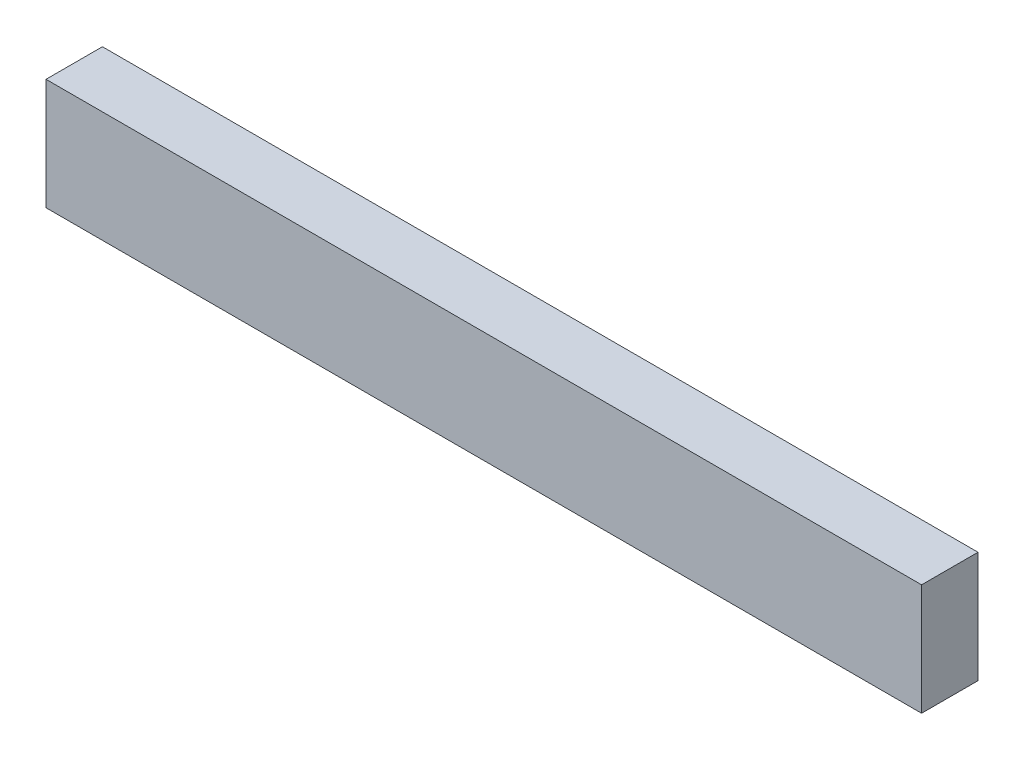
SolidWorks part; units mm, degrees
ref_plane "Přední rovina" through (0, 0, 0) normal (0, 0, 1) x (1, 0, 0)
ref_plane "Horní rovina" through (0, 0, 0) normal (0, 1, 0) x (1, 0, 0)
ref_plane "Pravá rovina" through (0, 0, 0) normal (1, 0, 0) x (0, 0, -1)
sketch "Skica1" plane through (0, 0, 0) normal (0, 0, 1) x (1, 0, 0)
  line L1 (-19.4, -2.465) -> (19.4, -2.465)
  line L2 (-19.4, -2.465) -> (-19.4, 2.465)
  line L3 (-19.4, 2.465) -> (19.4, 2.465)
  line L4 (19.4, -2.465) -> (19.4, 2.465)
  line L5 (-19.4, -2.465) -> (19.4, 2.465) construction
  line L6 (-19.4, 2.465) -> (19.4, -2.465) construction
  point P1 (0, 0)
  dimension "D1" = 38.8
  dimension "D2" = 4.93
extrude "Přidat vysunutím1" add sketch "Skica1" along normal blind 2.5
